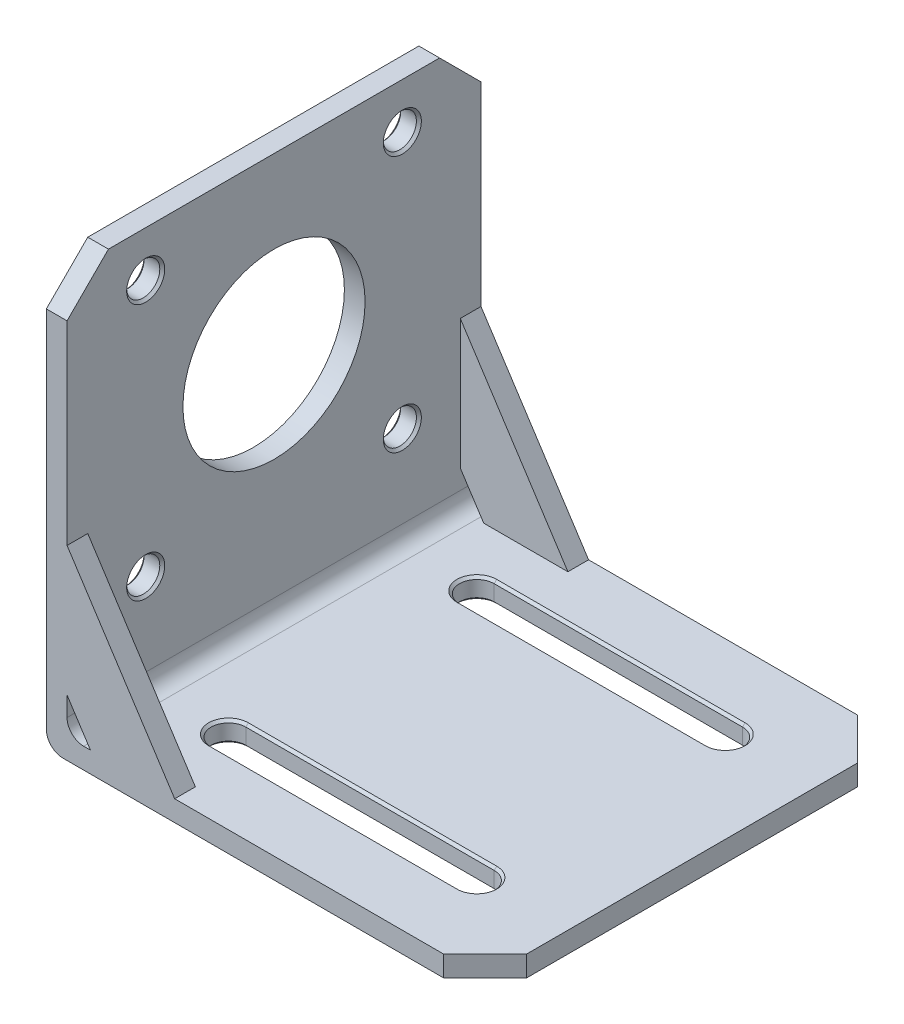
SolidWorks part; units mm, degrees
ref_plane "Front Plane" through (0, 0, 0) normal (0, 0, 1) x (1, 0, 0)
ref_plane "Top Plane" through (0, 0, 0) normal (0, 1, 0) x (1, 0, 0)
ref_plane "Right Plane" through (0, 0, 0) normal (1, 0, 0) x (0, 0, -1)
sketch "Sketch1" plane through (0, 0, 0) normal (0, 1, 0) x (1, 0, 0)
  line L1 (-26.5, 25) -> (26.5, 25)
  line L2 (-26.5, 25) -> (-26.5, -25)
  line L3 (-26.5, -25) -> (26.5, -25)
  line L4 (26.5, 25) -> (26.5, -25)
  line L5 (-26.5, 25) -> (26.5, -25) construction
  line L6 (-26.5, -25) -> (26.5, 25) construction
  point P0 (0, 0)
  dimension "D1" = 53
  dimension "D2" = 50
extrude "Boss-Extrude1" add sketch "Sketch1" along normal blind 2.5 contours L2 L3 L4 L1
sketch "Sketch2" plane through (-26.5, 0, 0) normal (-1, 0, 0) x (0, 0, 1)
  line L0 (-25, 0) -> (25, 0) construction
  line L1 (-25, 0) -> (25, 0)
  line L2 (-25, 0) -> (-25, 51)
  line L3 (-25, 51) -> (25, 51)
  line L4 (25, 0) -> (25, 51)
  dimension "D1" = 51
  dimension "D2" = 50
  dimension "D3" = 25
extrude "Boss-Extrude2" add sketch "Sketch2" against normal blind 2.5 contours L4 L3 L2 L1
chamfer "Chamfer1" distance 5 angle 45 4 edges at (-25.25, 51, -25) (-25.25, 51, 25) (26.5, 1.25, -25) (26.5, 1.25, 25)
sketch "Sketch3" plane through (-26.5, 0, 0) normal (-1, 0, 0) x (0, 0, 1)
  line L0 (-25, 46) -> (-25, 0) construction
  line L1 (-20, 51) -> (20, 51) construction
  circle A0 centre (0, 30) radius 11
  circle A1 centre (-15.5, 45.5) radius 2
  circle A2 centre (15.5, 45.5) radius 2
  circle A3 centre (-15.5, 14.5) radius 2
  circle A4 centre (15.5, 14.5) radius 2
  dimension "D2" = 22
  dimension "D4" = 4
  dimension "D5" = 15.5
  dimension "D6" = 15.5
  dimension "D7" = 31
  dimension "D8" = 31
  dimension "D9" = 31
  dimension "D10" = 4
  dimension "D11" = 4
  dimension "D12" = 4
  dimension "D13" = 31
  dimension "D14" = 15.5
  dimension "D15" = 15.5
  dimension "D1" = 25
  dimension "D3" = 21
extrude "Cut-Extrude1" cut sketch "Sketch3" against normal blind 2.5
sketch "Sketch4" plane through (0, 2.5, 0) normal (0, 1, 0) x (1, 0, 0)
  line L0 (-14.5, 15) -> (15.5, 15) construction
  line L1 (-14.5, 17.1) -> (15.5, 17.1)
  line L2 (-14.5, 12.9) -> (15.5, 12.9)
  line L3 (-14.5, -15) -> (15.5, -15) construction
  line L4 (-14.5, -12.9) -> (15.5, -12.9)
  line L5 (-14.5, -17.1) -> (15.5, -17.1)
  line L6 (26.5, 20) -> (26.5, -20) construction
  arc A0 (-14.5, 17.1) -> (-14.5, 12.9) centre (-14.5, 15) ccw
  arc A1 (15.5, 12.9) -> (15.5, 17.1) centre (15.5, 15) ccw
  arc A2 (-14.5, -12.9) -> (-14.5, -17.1) centre (-14.5, -15) ccw
  arc A3 (15.5, -17.1) -> (15.5, -12.9) centre (15.5, -15) ccw
  point P2 (0.5, 15)
  point P7 (0.5, -15)
  dimension "D2" = 11
  dimension "D5" = 2.1
  dimension "D8" = 2.1
  dimension "D1" = 11
  dimension "D3" = 30
  dimension "D4" = 15
  dimension "D6" = 30
  dimension "D7" = 30
extrude "Cut-Extrude2" cut sketch "Sketch4" against normal blind 2.5 contours L5 A3 L4 A2 | L2 A1 L1 A0
fillet "Fillet1" radius 2 1 edges at (-24, 2.5, 0)
fillet "Fillet2" radius 2 1 edges at (-26.5, 0, 0)
chamfer "Chamfer2" distance 0.3 angle 45 8 edges at (-24, 14.5, 17.5) (-24, 14.5, -13.5) (-24, 45.5, 17.5) (-24, 45.5, -13.5) (-26.5, 45.5, -13.5) (-26.5, 45.5, 17.5) (-26.5, 14.5, -13.5) (-26.5, 14.5, 17.5)
chamfer "Chamfer3" distance 0.3 angle 45 16 edges at (17.6, 0, 15) (0.5, 0, 17.1) (-16.6, 0, 15) (0.5, 0, 12.9) (0.5, 2.5, 17.1) (17.6, 2.5, 15) (0.5, 2.5, 12.9) (-16.6, 2.5, 15) (0.5, 0, -17.1) (17.6, 0, -15) (0.5, 0, -12.9) (-16.6, 0, -15) (17.6, 2.5, -15) (0.5, 2.5, -12.9) (-16.6, 2.5, -15) (0.5, 2.5, -17.1)
sketch "Sketch5" plane through (0, 0, 25) normal (0, 0, 1) x (1, 0, 0)
  line L0 (-24, 22.5) -> (-11, 2.5)
  line L1 (-24, 4.5) -> (-24, 46) construction
  line L2 (-22, 2.5) -> (21.5, 2.5) construction
  line L3 (-11, 2.5) -> (-21.1719, 2.5)
  line L4 (-24, 22.5) -> (-24, 6.8509)
  line L5 (-24, 6.8509) -> (-21.1719, 2.5)
  dimension "D1" = 13
  dimension "D2" = 20
extrude "Boss-Extrude3" add sketch "Sketch5" against normal blind 2.5
sketch "Sketch6" plane through (0, 0, -25) normal (0, 0, -1) x (-1, 0, 0)
  line L0 (24, 22.5) -> (11, 2.5)
  line L1 (11, 2.5) -> (21.1719, 2.5)
  line L2 (21.1719, 2.5) -> (24, 6.8509)
  line L3 (24, 6.8509) -> (24, 22.5)
extrude "Boss-Extrude4" add sketch "Sketch6" against normal blind 2.5
